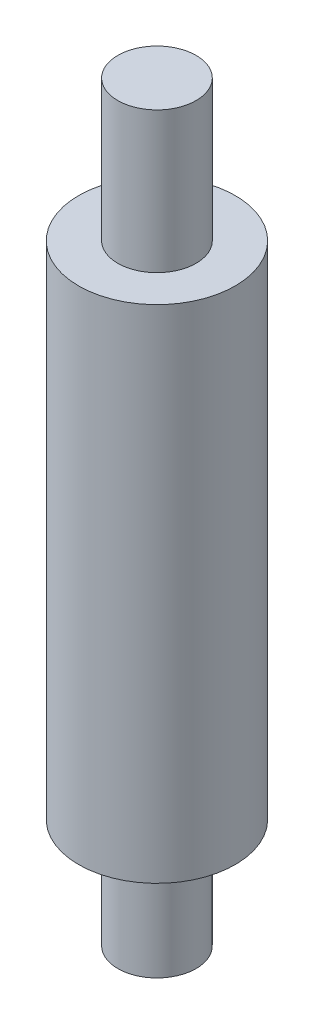
SolidWorks part; units mm, degrees
ref_plane "Front Plane" through (0, 0, 0) normal (0, 0, 1) x (1, 0, 0)
ref_plane "Top Plane" through (0, 0, 0) normal (0, 1, 0) x (1, 0, 0)
ref_plane "Right Plane" through (0, 0, 0) normal (1, 0, 0) x (0, 0, -1)
sketch "Sketch1" plane through (0, 0, 0) normal (0, 1, 0) x (1, 0, 0)
  circle A0 centre (0, 0) radius 2.5
  dimension "D1" = 5
extrude "Boss-Extrude1" add sketch "Sketch1" along normal blind 16 contours A0
sketch "Sketch2" plane through (0, 16, 0) normal (0, 1, 0) x (1, 0, 0)
  circle A0 centre (0, 0) radius 1.25
  dimension "D1" = 2.5
extrude "Boss-Extrude2" add sketch "Sketch2" along normal blind 4.5 contours A0
sketch "Sketch3" plane through (0, 0, 0) normal (0, -1, 0) x (-1, 0, 0)
  circle A0 centre (0, 0) radius 1.25
  dimension "D1" = 2.5
extrude "Boss-Extrude3" add sketch "Sketch3" along normal blind 3.5
